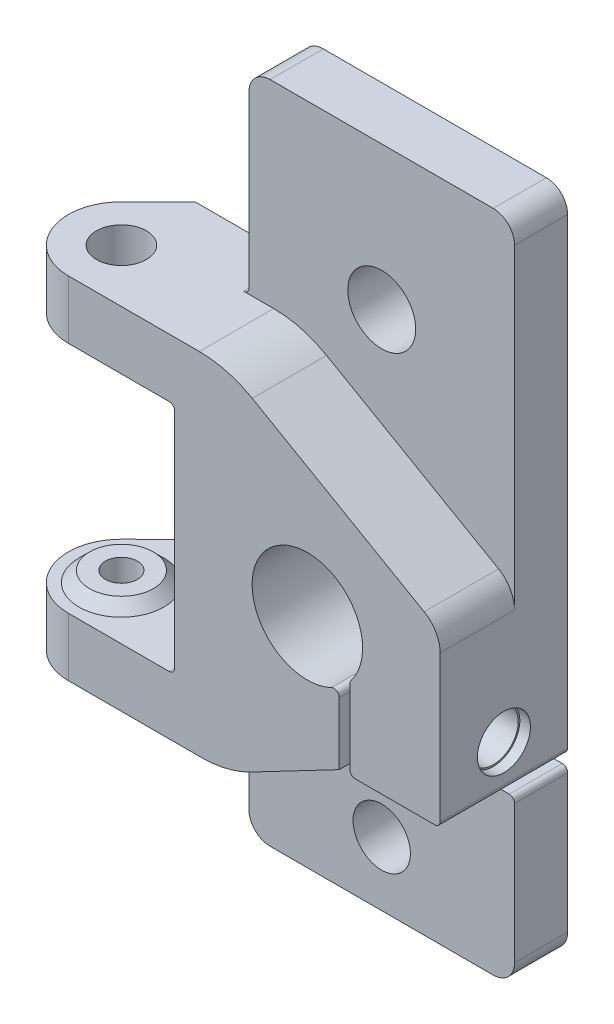
SolidWorks part; units mm, degrees
ref_plane "XY" through (0, 0, 0) normal (0, 0, 1) x (1, 0, 0)
ref_plane "XZ" through (0, 0, 0) normal (0, 1, 0) x (1, 0, 0)
ref_plane "YZ" through (0, 0, 0) normal (1, 0, 0) x (0, 0, -1)
sketch "Sketch1" plane through (0, 0, 0) normal (0, 0, 1) x (1, 0, 0)
  line L0 (5, 31.25) -> (5, -31.25)
  line L1 (20, 31.25) -> (5, 31.25) construction
  line L2 (20, 31.25) -> (20, -31.25) construction
  line L3 (20, -31.25) -> (5, -31.25) construction
  line L4 (-20, 31.25) -> (-20, -31.25)
  line L5 (20, 31.25) -> (-20, -31.25) construction
  line L6 (20, -31.25) -> (-20, 31.25) construction
  line L7 (5, 31.25) -> (-20, 31.25)
  line L8 (5, -31.25) -> (-20, -31.25)
  line L9 (-7.5, 31.25) -> (-7.5, -43.6532) construction
  line L10 (-20, -14.75) -> (-11.5, -14.75)
  line L11 (-11.5, -14.75) -> (-11.5, -7.0726)
  line L12 (-20, -15.75) -> (-10.5, -15.75)
  line L13 (-10.5, -15.75) -> (-10.5, -7.9974)
  line L14 (-10.5, -15.75) -> (-10.5, -7.0726) construction
  circle A0 centre (-7.5, 17.75) radius 3.2
  arc A1 (-10.5, -7.9974) -> (-11.5, -7.0726) centre (-7.5, -3.75) ccw
  circle A2 centre (-7.5, -25.25) radius 2.7
  point P0 (0, 0)
  dimension "D4" = 6.4
  dimension "D5" = 10.4
  dimension "D6" = 5.4
  dimension "D1" = 40
  dimension "D2" = 62.5
  dimension "D3" = 25
  dimension "D7" = 13.5
  dimension "D8" = 21.5
  dimension "D9" = 21.5
  dimension "D10" = 1
  dimension "D11" = 8.5
  dimension "D12" = 16.5
extrude "Boss-Extrude1" add sketch "Sketch1" along normal blind 5 contours A1 L13 L12 L4 L8 L0 L7 L10 L11 A2 A0
ref_plane "Plane1" through (0, 0, 12) normal (0, 0, 1) x (1, 0, 0)
sketch "Sketch2" plane through (0, 0, 12) normal (0, 0, 1) x (1, 0, 0)
  line L0 (0, 12.75) -> (20, 12.75)
  line L1 (20, -31.25) -> (-20, -31.25) construction
  line L2 (20, -31.25) -> (20, 31.25) construction
  line L3 (20, 31.25) -> (-20, 31.25) construction
  line L4 (-20, -31.25) -> (-20, 31.25) construction
  line L5 (20, -31.25) -> (-20, 31.25) construction
  line L6 (20, 31.25) -> (-20, -31.25) construction
  line L7 (20, 12.75) -> (20, 7.25)
  line L8 (20, 7.25) -> (5, 7.25)
  line L9 (-10.5, -7.9974) -> (-10.5, -15.75)
  line L10 (-10.5, -15.75) -> (-20, -15.75)
  line L11 (-20, -15.75) -> (-20, -31.25)
  line L12 (-20, -31.25) -> (5, -31.25)
  line L13 (5, -31.25) -> (5, 31.25)
  line L14 (5, 31.25) -> (-20, 31.25)
  line L15 (-20, 31.25) -> (-20, -14.75)
  line L16 (-20, -14.75) -> (-11.5, -14.75)
  line L17 (-11.5, -14.75) -> (-11.5, -7.0726)
  line L18 (-10.5, -7.9974) -> (-10.5, -14.75)
  line L19 (-10.5, -15.75) -> (-20, -15.75) construction
  line L20 (-7.5, -3.75) -> (38.2201, -3.75) construction
  line L21 (20, -14.75) -> (5, -14.75)
  line L22 (20, -20.25) -> (20, -14.75)
  line L23 (0, -20.25) -> (20, -20.25)
  line L24 (5, 31.25) -> (5, -31.25) construction
  line L25 (-20, -14.75) -> (-11.5, -14.75)
  line L26 (-11.5, -14.75) -> (-11.5, -7.0726)
  line L27 (5, 7.25) -> (5, -14.75)
  line L28 (0, 12.75) -> (-20, 1.25)
  line L29 (-20, 1.25) -> (-20, -14.75)
  line L30 (0, -20.25) -> (-10.5, -14.75)
  line L31 (-10.5, -14.75) -> (-10.5, -15.75) construction
  arc A1 (-10.5, -7.9974) -> (-11.5, -7.0726) centre (-7.5, -3.75) ccw
  arc A2 (-10.5, -7.9974) -> (-11.5, -7.0726) centre (-7.5, -3.75) ccw
  point P0 (0, 0)
  dimension "D2" = 18.5
  dimension "D3" = 5.5
  dimension "D4" = 20
  dimension "D5" = 30
  dimension "D1" = 0
extrude "Boss-Extrude2" add sketch "Sketch2" against normal up to surface (12 mm away) up to face at (-4.8, -25.25, 0)
sketch "Sketch3" plane through (0, -20.25, 0) normal (0, -1, 0) x (1, 0, 0)
  line L0 (15, 0) -> (20, 0)
  line L1 (20, 0) -> (5, 0) construction
  line L2 (20, 0) -> (20, 4.9)
  line L3 (20, 0) -> (20, 12) construction
  line L4 (20, 4.9) -> (15, 0)
  line L5 (15, 0) -> (15.0489, 0.0293)
  circle A0 centre (15, 7) radius 1.5
  dimension "D3" = 3
  dimension "D1" = 5
  dimension "D2" = 4.9
  dimension "D4" = 7
extrude "Cut-Extrude1" cut sketch "Sketch3" against normal through all
fillet "Fillet1" radius 4.9995 4 edges at (20, 10, 12) (20, 7.25, 8.45) (20, 12.75, 8.45) (20, 10, 4.9)
fillet "Fillet2" radius 4.9995 4 edges at (20, -17.5, 12) (20, -20.25, 8.45) (20, -14.75, 8.45) (20, -17.5, 4.9)
sketch "Sketch4" plane through (0, 7.25, 0) normal (0, -1, 0) x (1, 0, 0)
  circle A0 centre (15, 7) radius 3
  dimension "D1" = 6
extrude "Boss-Extrude3" add sketch "Sketch4" along normal blind 1
draft "Draft1" type of draft neutral plane draft angle 45 faces to draft 1 face at (18, 6.25, 7) neutral plane through (15, 6.25, 7) neutral plane normal (0, -1, 0) parameters "D1"=45
ref_plane "Plane2" through (0, -3.75, 0) normal (0, 1, 0) x (1, 0, 0)
mirror "Mirror1" about plane through (0, -3.75, 0) normal (0, 1, 0) of "Draft1", "Boss-Extrude3"
sketch "Sketch5" plane through (0, -20.25, 0) normal (0, -1, 0) x (1, 0, 0)
  circle A0 centre (15, 7) radius 1.5 construction
  circle A1 centre (15, 7) radius 1.5
extrude "Cut-Extrude2" cut sketch "Sketch5" against normal through all
sketch "Sketch6" plane through (0, -20.25, 0) normal (0, -1, 0) x (1, 0, 0)
  circle A0 centre (15, 7) radius 3.1
  dimension "D1" = 6.2
extrude "Cut-Extrude3" cut sketch "Sketch6" against normal blind 1.5
mirror "Mirror2" about plane through (0, -3.75, 0) normal (0, 1, 0) of "Cut-Extrude3"
fillet "Fillet3" radius 10 2 edges at (0, -20.25, 8.5) (0, 12.75, 8.5)
fillet "Fillet5" radius 0.5 9 edges at (-11.5, -7.0726, 6) (-11.5, -14.75, 6) (-20, -14.75, 6) (-20, -15.75, 2.5) (-10.5, -7.9974, 6) (5, 7.25, 6) (5, 12.75, 2.5) (5, -14.75, 6) (5, -20.25, 2.5)
fillet "Fillet6" radius 2 4 edges at (-20, 31.25, 2.5) (5, 31.25, 2.5) (5, -31.25, 2.5) (-20, -31.25, 2.5)
fillet "Fillet7" radius 3 1 edges at (-20, 1.25, 8.5)
ref_plane "Plane3" through (0, 0, 6) normal (0, 0, 1) x (1, 0, 0)
sketch "Sketch7" plane through (0, 0, 6) normal (0, 0, 1) x (1, 0, 0)
  line L0 (-28.8022, -10.75) -> (15.2765, -10.75) construction
  line L1 (5, -10.75) -> (5, -7.5)
  line L2 (5, -14.25) -> (5, 6.75) construction
  line L3 (5, -7.5) -> (2, -7.5)
  line L4 (2, -7.5) -> (2, -9)
  line L5 (2, -9) -> (-15, -9)
  line L8 (-20, -10.75) -> (5, -10.75)
  line L12 (-15, -9) -> (-15, -8.4)
  line L13 (-15, -8.4) -> (-19, -8.4)
  line L14 (-19, -8.4) -> (-19, -8.25)
  line L15 (-19, -8.25) -> (-20, -8.25)
  line L16 (-20, -0.4856) -> (-20, -14.25) construction
  line L17 (-20, -8.25) -> (-20, -10.75)
  dimension "D1" = 10.75
  dimension "D2" = 3.25
  dimension "D3" = 1.75
  dimension "D4" = 3
  dimension "D5" = 2.5
  dimension "D6" = 1
  dimension "D7" = 2.35
  dimension "D8" = 4
revolve "Cut-Revolve3" cut sketch "Sketch7" angle 360 about L0
sketch "Sketch8" plane through (0, 12.75, 0) normal (0, 1, 0) x (1, 0, 0)
  circle A0 centre (15, -7) radius 3.1
  circle A1 centre (15, -7) radius 2.35
  dimension "D1" = 4.7
  dimension "D2" = 6.2
extrude "Boss-Extrude4" add sketch "Sketch8" against normal up to surface (1.5 mm away) up to face at (15, 11.25, 3.9)
sketch "Sketch9" plane through (0, 11.25, 0) normal (0, 1, 0) x (1, 0, 0)
  circle A0 centre (15, -7) radius 2.35 construction
  circle A1 centre (15, -7) radius 2.35
  circle A2 centre (15, -7) radius 1.5
extrude "Cut-Extrude4" cut sketch "Sketch9" against normal blind 4
mirror "Mirror3" about plane through (0, 0, 0) normal (1, 0, 0) of bodies 128
delete or keep bodies "Body-Delete1" type delete bodies bodies 128
